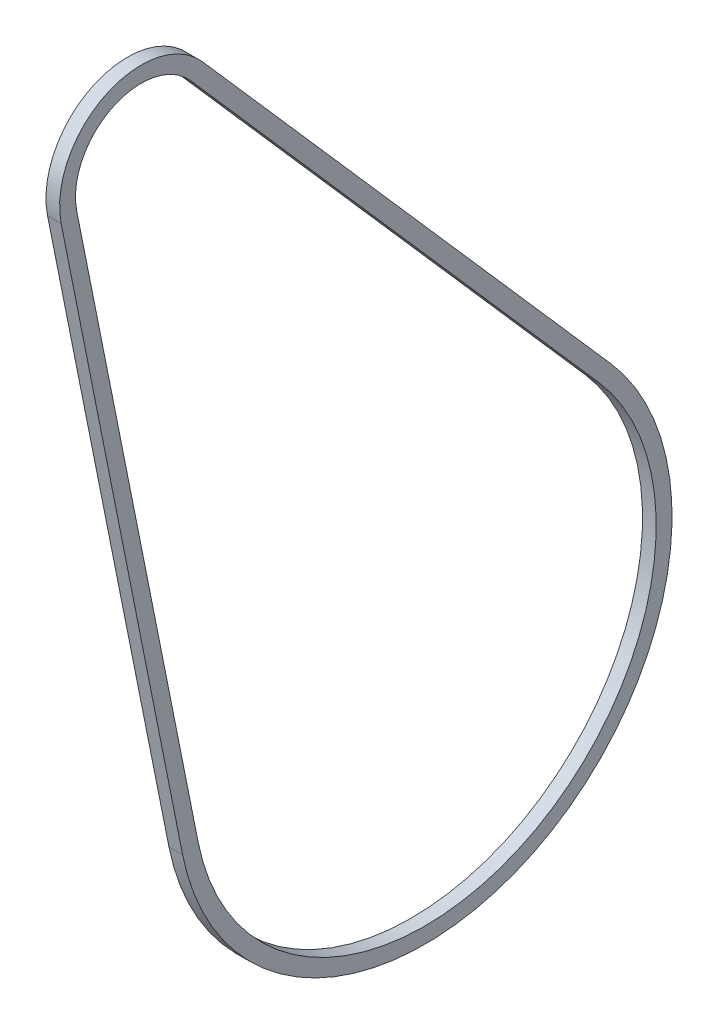
SolidWorks part; units mm, degrees
ref_plane "Front Plane" through (0, 0, 0) normal (0, 0, 1) x (1, 0, 0)
ref_plane "Top Plane" through (0, 0, 0) normal (0, 1, 0) x (1, 0, 0)
ref_plane "Right Plane" through (0, 0, 0) normal (1, 0, 0) x (0, 0, -1)
sketch "Sketch1" plane through (120.8182, 0, 0) normal (1, 0, 0) x (0, 0, -1)
  line L0 (840.8096, 489.5906) -> (1035.0338, 268.1052)
  line L1 (786.7051, 462.8767) -> (844.4641, 174.0122)
  line L2 (846.4787, 494.5619) -> (1040.7028, 273.0765)
  line L3 (779.3115, 461.3983) -> (837.0704, 172.5339)
  circle A0 centre (817.329, 469) radius 31.23 construction
  circle A1 centre (952.329, 195.58) radius 110 construction
  arc A2 (786.7051, 462.8767) -> (840.8096, 489.5906) centre (817.329, 469) cw
  arc A3 (1035.0338, 268.1052) -> (844.4641, 174.0122) centre (952.329, 195.58) cw
  arc A4 (1040.7028, 273.0765) -> (837.0704, 172.5339) centre (952.329, 195.58) cw
  arc A5 (779.3115, 461.3983) -> (846.4787, 494.5619) centre (817.329, 469) cw
  dimension "D1" = 7.54
extrude "Boss-Extrude1" add sketch "Sketch1" against normal blind 6.5
ref_plane "Plane1" through (117.5682, 0, 0) normal (-1, 0, 0) x (0, 0, 1)
